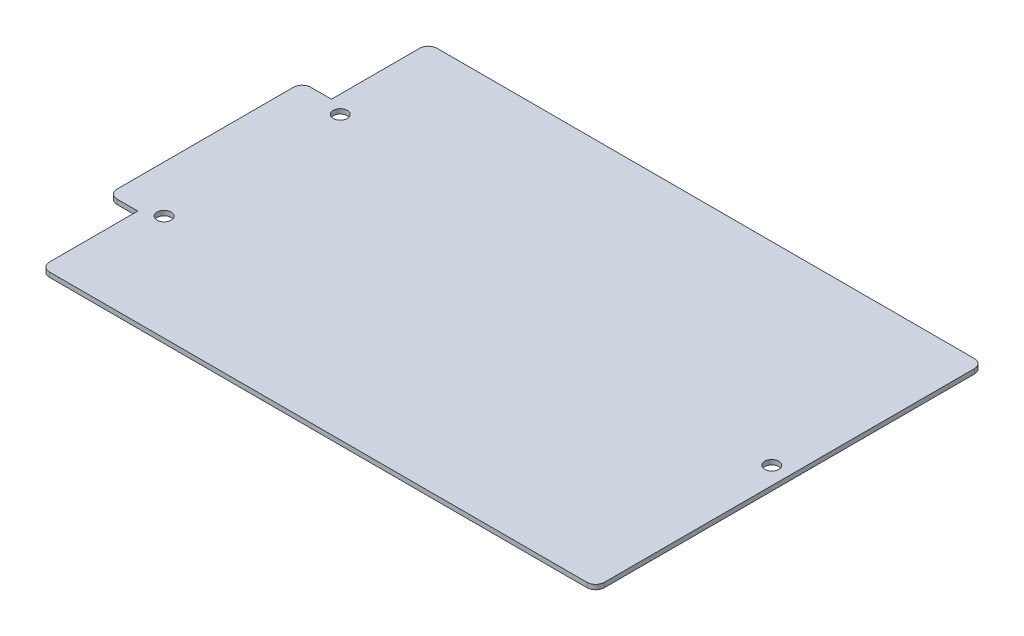
SolidWorks part; units mm, degrees
material "Copper"
ref_plane "Front Plane" through (0, 0, 0) normal (0, 0, 1) x (1, 0, 0)
ref_plane "Top Plane" through (0, 0, 0) normal (0, 1, 0) x (1, 0, 0)
ref_plane "Right Plane" through (0, 0, 0) normal (1, 0, 0) x (0, 0, -1)
sketch "Sketch1" plane through (0, 0, 0) normal (0, 1, 0) x (1, 0, 0)
  line L0 (0, 66) -> (189, 66) construction
  line L1 (0, 132) -> (189, 132)
  line L2 (0, 132) -> (0, 0) construction
  line L3 (0, 0) -> (189, 0)
  line L4 (189, 132) -> (189, 0)
  line L5 (6, 36) -> (6, 96) construction
  line L6 (0, 132) -> (-10, 132)
  line L7 (-10, 132) -> (-10, 0)
  line L8 (-10, 0) -> (0, 0)
  circle A0 centre (6, 96) radius 2.4
  circle A1 centre (6, 36) radius 2.4
  circle A2 centre (183, 66) radius 2.4
  dimension "D4" = 4.8
  dimension "D1" = 189
  dimension "D2" = 132
  dimension "D3" = 6
  dimension "D5" = 6
  dimension "D6" = 60
  dimension "D7" = 10
extrude "Boss-Extrude1" add sketch "Sketch1" along normal blind 1.6
ref_plane "Plane1" through (0, 0, -66) normal (0, 0, 1) x (1, 0, 0)
sketch "Sketch2" plane through (0, 1.6, 0) normal (0, 1, 0) x (1, 0, 0)
  line L1 (-10, 132) -> (0, 132)
  line L2 (-10, 132) -> (-10, 99)
  line L3 (-10, 99) -> (0, 99)
  line L4 (0, 132) -> (0, 99)
  dimension "D1" = 10
  dimension "D2" = 33
extrude "Cut-Extrude1" cut sketch "Sketch2" against normal up to next
mirror "Mirror1" about plane through (0, 0, -66) normal (0, 0, 1) of "Cut-Extrude1"
fillet "Fillet1" radius 3 6 edges at (-10, 0.8, -33) (0, 0.8, 0) (189, 0.8, 0) (189, 0.8, -132) (0, 0.8, -132) (-10, 0.8, -99)
